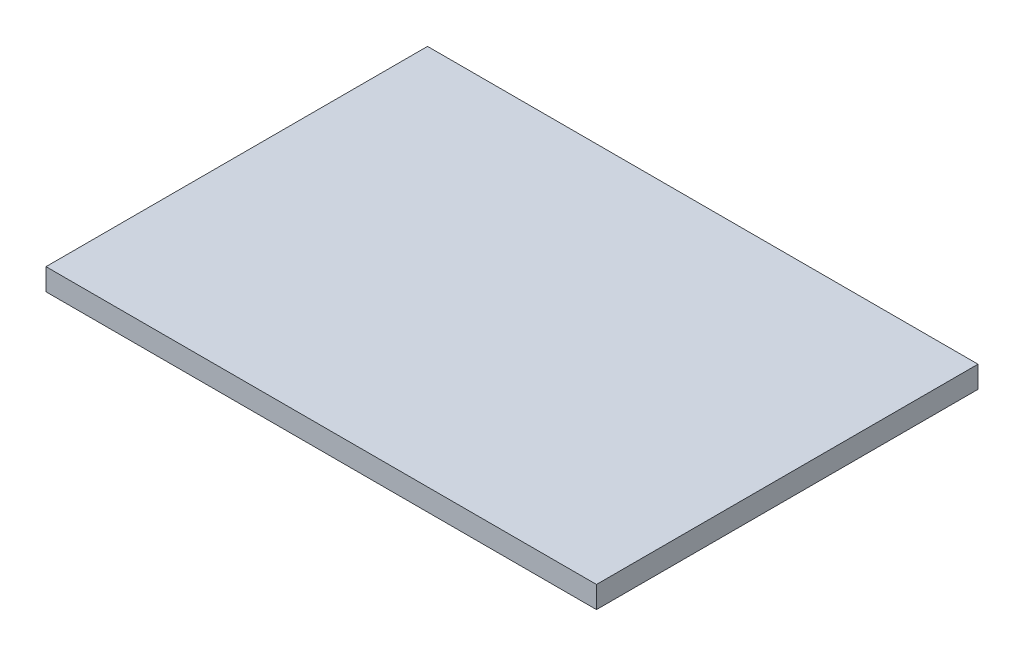
SolidWorks part; units mm, degrees
material "Plain Carbon Steel"
ref_plane "Front Plane" through (0, 0, 0) normal (0, 0, 1) x (1, 0, 0)
ref_plane "Top Plane" through (0, 0, 0) normal (0, 1, 0) x (1, 0, 0)
ref_plane "Right Plane" through (0, 0, 0) normal (1, 0, 0) x (0, 0, -1)
sketch "Sketch1" plane through (0, 0, 0) normal (1, 0, 0) x (0, 0, -1)
  line L1 (-350, -20) -> (350, -20)
  line L2 (-350, -20) -> (-350, 20)
  line L3 (-350, 20) -> (350, 20)
  line L4 (350, -20) -> (350, 20)
  line L5 (-350, -20) -> (350, 20) construction
  line L6 (-350, 20) -> (350, -20) construction
  point P0 (0, 0)
  dimension "D1" = 700
  dimension "D2" = 40
extrude "Boss-Extrude1" add sketch "Sketch1" along normal mid plane 1010
